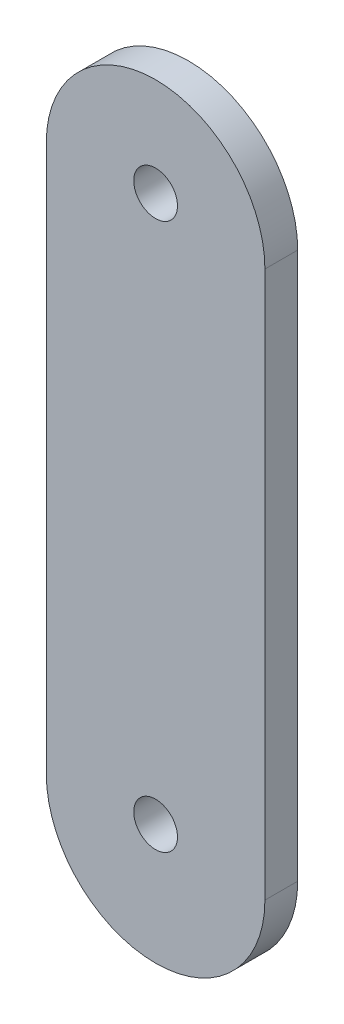
SolidWorks part; units mm, degrees
ref_plane "Front Plane" through (0, 0, 0) normal (0, 0, 1) x (1, 0, 0)
ref_plane "Top Plane" through (0, 0, 0) normal (0, 1, 0) x (1, 0, 0)
ref_plane "Right Plane" through (0, 0, 0) normal (1, 0, 0) x (0, 0, -1)
sketch "Sketch1" plane through (0, 0, 0) normal (0, 0, 1) x (1, 0, 0)
  line L0 (0, 25) -> (0, -25) construction
  line L1 (10, 25) -> (10, -25)
  line L2 (-10, 25) -> (-10, -25)
  arc A0 (10, 25) -> (-10, 25) centre (0, 25) ccw
  arc A1 (-10, -25) -> (10, -25) centre (0, -25) ccw
  circle A2 centre (0, 26) radius 2
  circle A3 centre (0, -24) radius 2
  point P3 (0, 0)
  dimension "D1" = 10
  dimension "D3" = 4
  dimension "D2" = 50
  dimension "D4" = 50
  dimension "D5" = 1
extrude "Boss-Extrude1" add sketch "Sketch1" along normal blind 3
